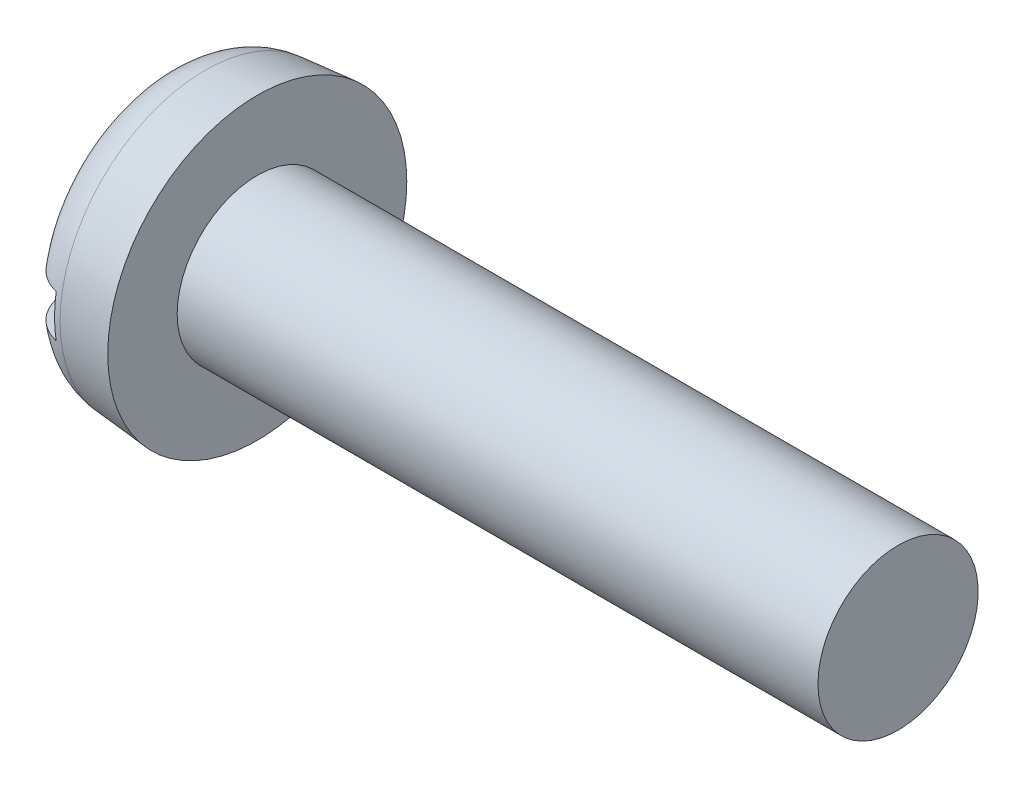
SolidWorks part; units mm, degrees
ref_plane "Plane1" through (0, 0, 0) normal (0, 0, 1) x (1, 0, 0)
ref_plane "Plane2" through (0, 0, 0) normal (0, 1, 0) x (1, 0, 0)
ref_plane "Plane3" through (0, 0, 0) normal (1, 0, 0) x (0, 0, -1)
sketch "BodySke" plane through (0, 0, 0) normal (0, 0, 1) x (1, 0, 0)
  line L0 (1.8, 1.5) -> (1.8, 2.8)
  line L1 (0, 0) -> (0, 2.6425)
  line L2 (-25.4, 0) -> (127, 0) construction
  line L3 (13.8, 0) -> (0, 0)
  line L4 (1.8, 1.5) -> (13.8, 1.5)
  line L5 (13.8, 1.5) -> (13.8, 0)
  line L6 (0, 2.6425) -> (1.8, 2.8)
  line L9 (2.3, 3.0875) -> (2.3, -6.4375) construction
  line L10 (1.8, 6.35) -> (1.8, -3.175) construction
  dimension "Length" = 12
  dimension "Head_ht" = 1.8
  dimension "Advance" = 0.5
  dimension "Thread_nom" = 12
  dimension "Head_dia" = 5.6
  dimension "Head_side_angle" = 5
  dimension "Diameter" = 3
revolve "Base-Revolve" add sketch "BodySke"
cosmetic thread "ThreadCosmetic" [suppressed]
fillet "Fillet1" [suppressed] radius 0.1
fillet "Fillet2" radius 0.9 1 edges at (0, 0, 2.6425)
sketch "Sketch2" plane through (0, 0, 0) normal (1, 0, 0) x (0, 0, -1)
  line L0 (2.8, -0.4) -> (-2.8, -0.4)
  line L1 (2.8, -0.4) -> (2.8, 0.4)
  line L2 (-2.8, 0.4) -> (2.8, 0.4)
  line L3 (-2.8, 0.4) -> (-2.8, -0.4)
  dimension "D1" = 5.6
  dimension "Slot_width" = 0.8
  dimension "D2" = 2.8
  dimension "D3" = 0.4
extrude "Slot" cut sketch "Sketch2" along normal blind 0.7
sketch "ThdSchSke" plane through (0, 0, 0) normal (0, 0, 1) x (1, 0, 0)
  line L0 (2.8, -1.2195) -> (2.6036, -1.5)
  line L1 (2.8, -1.2195) -> (2.9964, -1.5)
  line L2 (2.9964, -1.5) -> (2.9964, -1.875)
  line L3 (-3.175, 0) -> (5.1513, 0) construction
  line L5 (2.9964, -1.875) -> (2.6036, -1.875)
  line L6 (2.6036, -1.875) -> (2.6036, -1.5)
  dimension "Diameter" = 3
  dimension "SideAngle" = 55
  dimension "VeeAngle" = 70
  dimension "Thread_minor" = 2.439
  dimension "Overcut" = 3.75
  dimension "Start" = 2.8
revolve "ThreadSchematic" [suppressed] cut sketch "ThdSchSke" angle 360 about L3
pattern_linear "ThdSchPat" [suppressed]
equation "\"D1@Sketch2\" = \"Head_dia@BodySke\""
equation "\"D2@Sketch2\" = \"D1@Sketch2\" / 2"
equation "\"D3@Sketch2\" = \"Slot_width@Sketch2\" / 2"
equation "\"Thread_length@ThreadCosmetic\" = ((sgn( (\"Length@BodySke\" - \"Advance@BodySke\" * 2.0 ) - \"Thread_nom@BodySke\" )-1)*( (\"Length@BodySke\" - \"Advance@BodySke\"  * 2.0) - \"Thread_nom@BodySke\" ))/-2+ \"Thread_nom@BodySke\""
equation "\"Thread_minor@ThdSchSke\" = \"Thread_minor@ThreadCosmetic\""
equation "\"Diameter@ThdSchSke\" = \"Diameter@BodySke\""
equation "\"Overcut@ThdSchSke\" = \"Diameter@BodySke\" * 1.25"
equation "\"Start@ThdSchSke\" = \"Head_ht@BodySke\" + \"Length@BodySke\" - \"Thread_length@ThreadCosmetic\"  '---Non-countersunk---"
equation "\"Num_threads@ThdSchPat\" = int( \"Thread_length@ThreadCosmetic\" / \"Advance@BodySke\" + 0.999 )  + 1"
equation "\"Advance@ThdSchPat\" = \"Thread_length@ThreadCosmetic\" /  (\"Num_threads@ThdSchPat\" - 1) 'relax it"
